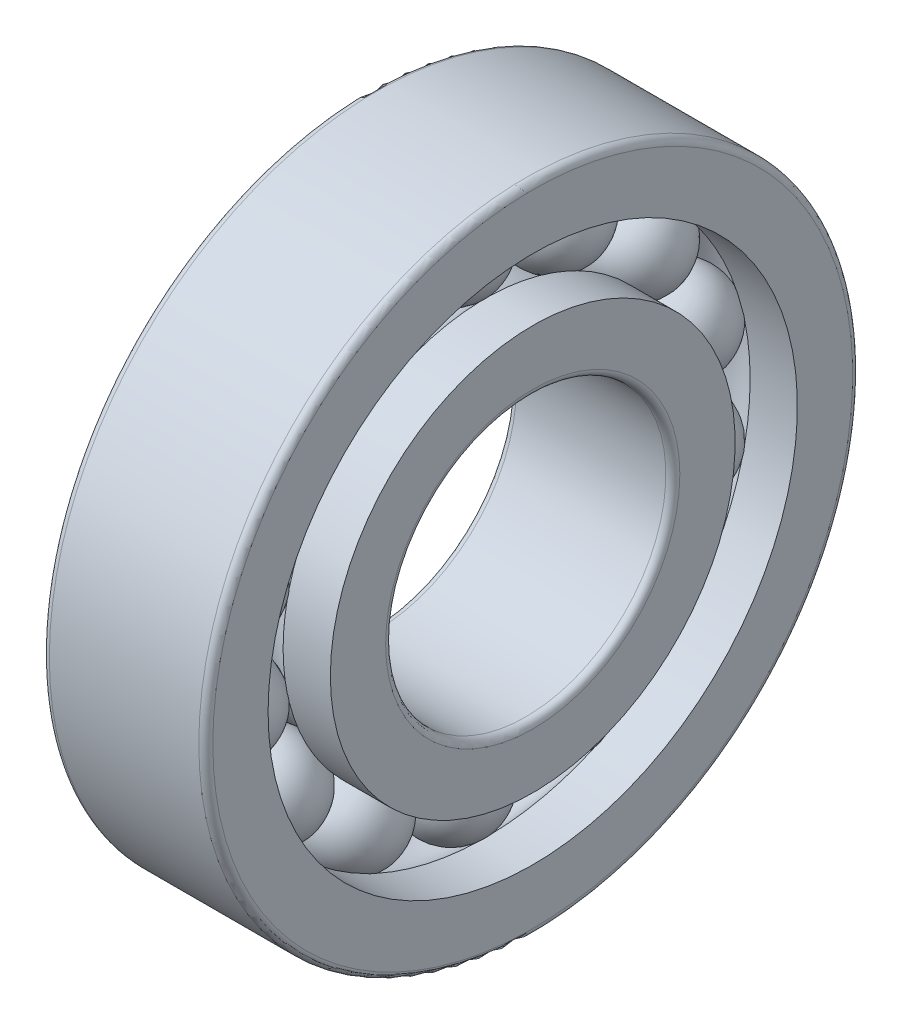
SolidWorks part; units mm, degrees
ref_plane "Front" through (0, 0, 0) normal (0, 0, 1) x (1, 0, 0)
ref_plane "Top" through (0, 0, 0) normal (0, 1, 0) x (1, 0, 0)
ref_plane "Right" through (0, 0, 0) normal (1, 0, 0) x (0, 0, -1)
other "Configuration Table"
sketch "Sketch1" plane through (0, 0, 0) normal (0, 0, 1) x (1, 0, 0)
  line L0 (-9.6833, 0) -> (9.8371, 0) construction
  line L1 (-2, 10) -> (2, 10)
  line L2 (-4.5966, 10) -> (4.6657, 10) construction
  arc A0 (2, 10) -> (-2, 10) centre (0, 10) ccw
revolve "Revolve1" add sketch "Sketch1" angle 360 about L2
sketch "Sketch2" plane through (0, 0, 0) normal (0, 0, 1) x (1, 0, 0)
  line L0 (-3.5, 8.6667) -> (-3.5, 6)
  line L1 (-3.5, 6) -> (3.5, 6)
  line L2 (3.5, 6) -> (3.5, 8.6667)
  line L3 (3.5, 8.6667) -> (1.4773, 8.6667)
  line L4 (-6.9714, 0) -> (8.1665, 0) construction
  line L5 (-6.7058, 10) -> (6.7058, 10) construction
  line L6 (-1.4773, 8.6667) -> (-3.5, 8.6667)
  arc A0 (-1.4773, 8.6667) -> (1.4773, 8.6667) centre (0, 10) ccw
  dimension "B" = 7
  dimension "B/2" = 3.5
revolve "Revolve2" add sketch "Sketch2" angle 360 about L4
sketch "Sketch3" plane through (0, 0, 0) normal (0, 0, 1) x (1, 0, 0)
  line L0 (-8.7107, 0) -> (9.1288, 0) construction
  line L1 (-3.5, 14) -> (3.5, 14)
  line L2 (-3.5, 14) -> (-3.5, 11.3333)
  line L3 (-3.5, 11.3333) -> (-1.4773, 11.3333)
  line L4 (3.5, 14) -> (3.5, 11.3333)
  line L5 (-7.2948, 10) -> (7.2948, 10) construction
  line L6 (1.4773, 11.3333) -> (3.5, 11.3333)
  arc A0 (1.4773, 11.3333) -> (-1.4773, 11.3333) centre (0, 10) ccw
  dimension "DD" = 28
  dimension "B" = 7
  dimension "B/2" = 3.5
revolve "Revolve3" add sketch "Sketch3" angle 360 about L0
pattern_circular "Circular-Pattern1" count 14 over 360 about axis through (0, 0, 0) along (1, 0, 0) of "Revolve1"
fillet "Fillet1" radius 0.3 4 edges at (-3.5, 0, 6) (-3.5, 0, 14) (3.5, 0, 14) (3.5, 0, 6)
equation "\"d0@Sketch1\" = ( \"DD@Sketch3\" + \"d@Sketch2\" )  / 2"
equation "\"dia@Sketch1\" =  ( \"DD@Sketch3\" - \"d@Sketch2\" )  / 4"
equation "\"D3@Sketch2\" = ( \"DD@Sketch3\" + \"d@Sketch2\" )  / 2 / 2"
equation "\"D4@Sketch2\" = ( \"DD@Sketch3\" - \"d@Sketch2\" )  / 6"
equation "\"D5@Sketch2\" = \"dia@Sketch1\" - 0.02"
equation "\"B/2@Sketch2\" = \"B@Sketch2\" / 2"
equation "\"D4@Sketch3\" = ( \"DD@Sketch3\" + \"d@Sketch2\" )  / 2 / 2"
equation "\"D5@Sketch3\" = ( \"DD@Sketch3\" - \"d@Sketch2\" )  / 6"
equation "\"B@Sketch3\" = \"B@Sketch2\""
equation "\"B/2@Sketch3\" = \"B@Sketch3\" / 2"
equation "\"D1@Sketch3\" = \"dia@Sketch1\" - 0.02"
equation "\"m@Circular-Pattern1\" = int( 3.14159265 / atn(( \"dia@Sketch1\" / 2) / sqr(( \"DD@Sketch3\" + \"d@Sketch2\" )  / 2 * ( \"DD@Sketch3\" + \"d@Sketch2\" )  / 2/4 - ( \"dia@Sketch1\" / 2) *  ( \"dia@Sketch1\" / 2))))-1"
